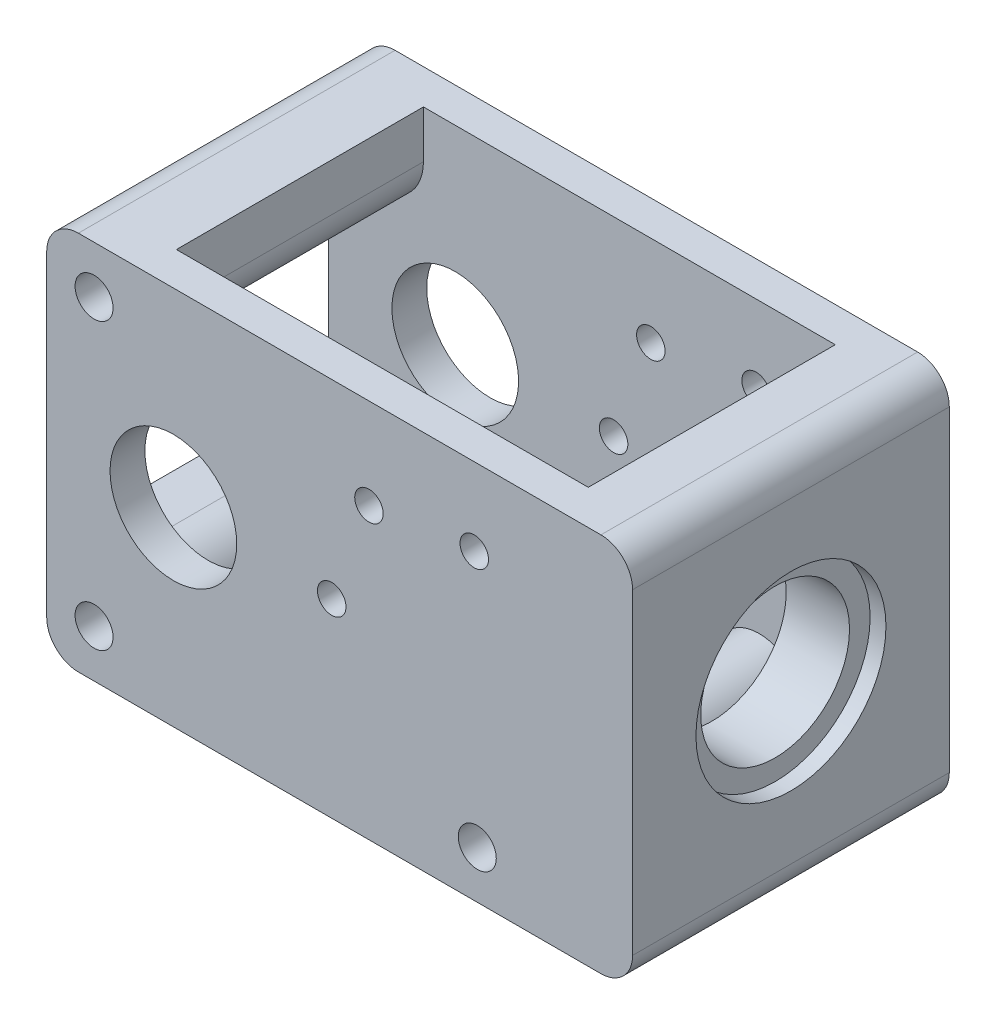
SolidWorks part; units mm, degrees
other "MotorGearBox"
material "Nylon 101"
ref_plane "Front" through (0, 0, 0) normal (0, 0, 1) x (1, 0, 0)
ref_plane "Top" through (0, 0, 0) normal (0, 1, 0) x (1, 0, 0)
ref_plane "Right" through (0, 0, 0) normal (1, 0, 0) x (0, 0, -1)
sketch "BodySke" plane through (0, 0, 0) normal (0, 0, 1) x (1, 0, 0)
  line L0 (0, 0) -> (5, 0) construction
  line L1 (-4, -6) -> (-4, 6) construction
  line L2 (-4, 6) -> (12, 6) construction
  line L3 (12, 6) -> (12, 4) construction
  line L4 (12, 4) -> (14.5, 4) construction
  line L5 (14.5, 4) -> (14.5, -4) construction
  line L6 (14.5, -4) -> (12, -4) construction
  line L7 (12, -4) -> (12, -6) construction
  line L8 (12, -6) -> (-4, -6) construction
  line L9 (-2.5045, 4.5) -> (-2.5045, -4.5) construction
  line L10 (-2.5045, 4.5) -> (0, 0) construction
  line L11 (0, 0) -> (-2.5045, -4.5) construction
  line L13 (5, 0) -> (6.1756, 3.137) construction
  line L14 (6.1756, 3.137) -> (9.5, 3.55) construction
  line L16 (11.5, -1.6) -> (7.5, -1.6) construction
  line L17 (11.5, -1.6) -> (11.5, 1.6) construction
  line L18 (11.5, 1.6) -> (7.5, 1.6) construction
  line L19 (7.5, -1.6) -> (7.5, 1.6) construction
  line L20 (11.5, -1.6) -> (7.5, 1.6) construction
  line L21 (11.5, 1.6) -> (7.5, -1.6) construction
  line L23 (-4, -6) -> (-4, 6) construction
  line L30 (-3, 6) -> (13.5, 6)
  line L31 (-4, 5) -> (-4, -5)
  line L32 (-3, -6) -> (13.5, -6)
  line L33 (14.5, 5) -> (14.5, -5)
  circle A0 centre (0, 0) radius 2
  circle A1 centre (5, 0) radius 0.45
  circle A2 centre (-2.5045, 4.5) radius 0.6
  circle A3 centre (-2.5045, -4.5) radius 0.6
  circle A6 centre (6.1756, 3.137) radius 0.45
  circle A7 centre (9.5, 3.55) radius 0.45
  circle A8 centre (0, 0) radius 3.415 construction
  circle A9 centre (5, 0) radius 2.364 construction
  circle A10 centre (6.1756, 3.137) radius 2.47 construction
  circle A11 centre (9.5, 3.55) radius 2.205 construction
  circle A12 centre (5, 0) radius 1.8 construction
  circle A13 centre (6.1756, 3.137) radius 1.194 construction
  circle A14 centre (9.5, 3.55) radius 1.1275 construction
  circle A15 centre (9.5955, -4.5) radius 0.6
  arc A16 (13.5, 6) -> (14.5, 5) centre (13.5, 5) cw
  arc A17 (13.5, -6) -> (14.5, -5) centre (13.5, -5) ccw
  arc A18 (-4, -5) -> (-3, -6) centre (-3, -5) ccw
  arc A19 (-3, 6) -> (-4, 5) centre (-3, 5) ccw
  point P13 (-4, 0)
  point P18 (-2.5045, 0)
  point P24 (14.5, -6)
  point P50 (9.5, 0)
  dimension "D1" = 4
  dimension "D3" = 0.9
  dimension "D11" = 1.2
  dimension "D12" = 1
  dimension "D16" = 6.83
  dimension "D17" = 4.728
  dimension "D18" = 4.94
  dimension "D19" = 4.41
  dimension "D20" = 3.6
  dimension "D21" = 2.388
  dimension "D22" = 2.255
  dimension "D2" = 5
  dimension "D4" = 4
  dimension "D5" = 8
  dimension "D6" = 2.5
  dimension "D7" = 16
  dimension "D8" = 12
  dimension "D9" = 9
  dimension "D10" = 5.15
  dimension "D14" = 3.35
  dimension "D15" = 3.35
  dimension "D23" = 3
  dimension "D24" = 7
  dimension "D25" = 3.2
  dimension "D26" = 2.45
  dimension "D27" = 12.1
extrude "Body" add sketch "BodySke" along normal mid plane 10
sketch "BoxSke" plane through (0, 0, 0) normal (0, 0, 1) x (1, 0, 0)
  line L0 (12, 6) -> (12, -6)
  line L1 (13.5, 6) -> (-3, 6) construction
  line L2 (-3, -6) -> (13.5, -6) construction
  line L3 (12, -6) -> (-1.0045, -6)
  line L4 (12, 6) -> (-1.0045, 6)
  line L6 (12, 6) -> (12, 4) construction
  line L7 (-2.5045, 4.5) -> (-2.5045, -4.5) construction
  line L8 (-1.0045, -4.5) -> (-1.0045, -6)
  line L9 (-2.5045, -3) -> (-4, -3)
  line L10 (-4, 5) -> (-4, -5) construction
  line L11 (-4, -3) -> (-4, 3)
  line L12 (-4, 3) -> (-2.5045, 3)
  line L13 (-1.0045, 4.5) -> (-1.0045, 6)
  line L14 (-3, 6) -> (13.5, 6) construction
  arc A0 (-2.5045, -3) -> (-1.0045, -4.5) centre (-2.5045, -4.5) cw
  arc A1 (-1.0045, 4.5) -> (-2.5045, 3) centre (-2.5045, 4.5) cw
  circle A2 centre (9.5955, -4.5) radius 1.4
  dimension "D1" = 1.5
  dimension "D2" = 2.8
extrude "Box" cut sketch "BoxSke" against normal mid plane 7.8
sketch "HoleSke" plane through (14.5, 0, 0) normal (1, 0, 0) x (0, 0, -1)
  circle A0 centre (0, 0) radius 2.35
  dimension "D1" = 4.7
extrude "Hole" cut sketch "HoleSke" against normal through all
sketch "PadSke" plane through (14.5, 0, 0) normal (1, 0, 0) x (0, 0, -1)
  circle A0 centre (0, 0) radius 3
  dimension "D1" = 6
extrude "Pad" cut sketch "PadSke" against normal blind 0.5
